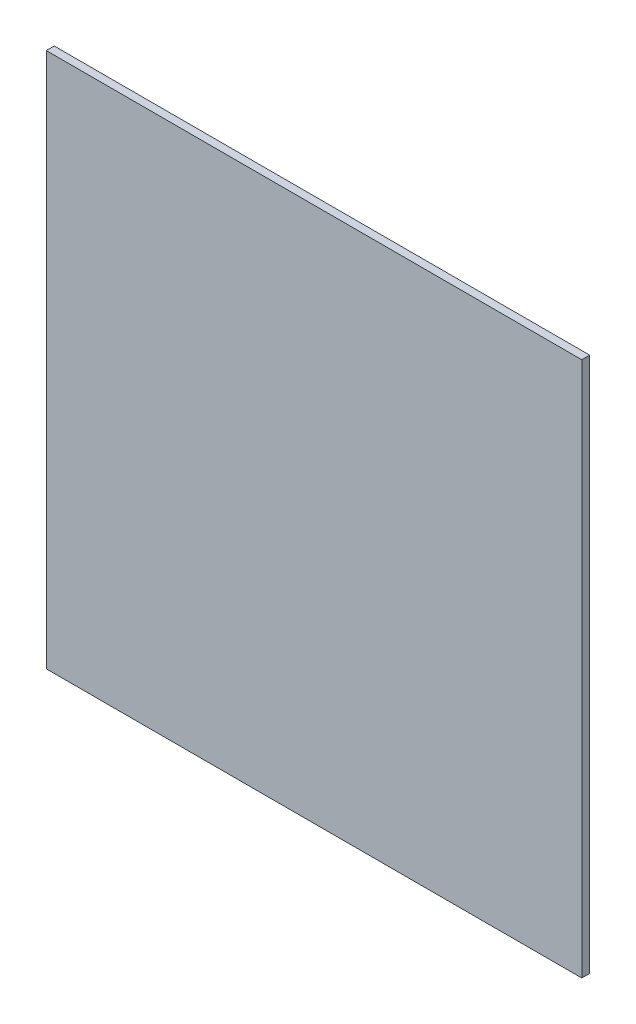
SolidWorks part; units mm, degrees
ref_plane "Front Plane" through (0, 0, 0) normal (0, 0, 1) x (1, 0, 0)
ref_plane "Top Plane" through (0, 0, 0) normal (0, 1, 0) x (1, 0, 0)
ref_plane "Right Plane" through (0, 0, 0) normal (1, 0, 0) x (0, 0, -1)
sketch "Sketch1" plane through (0, 0, 0) normal (0, 0, 1) x (1, 0, 0)
  line L1 (0, 0) -> (27, 0)
  line L2 (0, 0) -> (0, 27)
  line L3 (0, 27) -> (27, 27)
  line L4 (27, 0) -> (27, 27)
  dimension "D1" = 27
extrude "Profile" add sketch "Sketch1" along normal blind 0.4
equation "\"Profile_Depth\" = 0.4mm"
equation "\"D1@Profile\" = \"Profile_Depth\""
equation "\"EnvelopeWidth\" = 27mm"
equation "\"EnvelopeHeight\" = 27mm"
